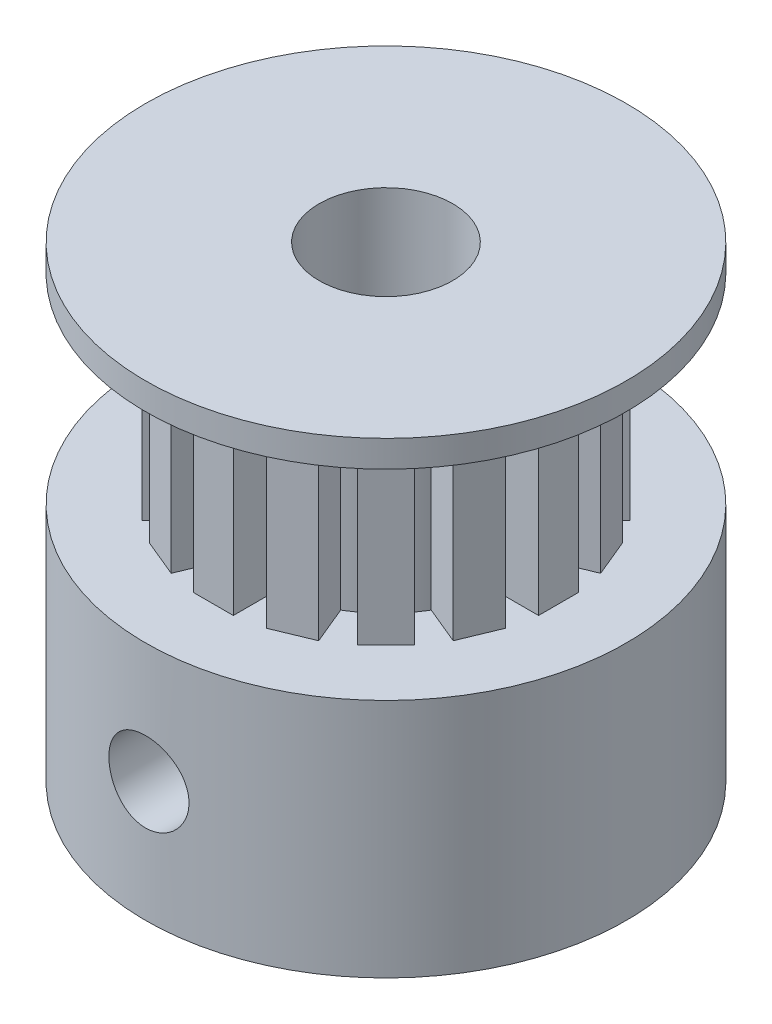
SolidWorks part; units mm, degrees
material "Liga 1060"
ref_plane "Plano frontal" through (0, 0, 0) normal (0, 0, 1) x (1, 0, 0)
ref_plane "Plano superior" through (0, 0, 0) normal (0, 1, 0) x (1, 0, 0)
ref_plane "Plano direito" through (0, 0, 0) normal (1, 0, 0) x (0, 0, -1)
sketch "Esboço1" plane through (0, 0, 0) normal (0, 0, 1) x (1, 0, 0)
  line L0 (0, 17.5) -> (0, 0)
  line L3 (-5, 0) -> (0, 0)
  line L7 (-9, 9) -> (-5, 9)
  line L8 (-9, 9) -> (-9, 8)
  line L11 (-9, 8) -> (-9, 0)
  line L12 (-9, 0) -> (-5, 0)
  line L14 (-5, 16.5) -> (-5, 9)
  line L19 (-9, 17.5) -> (0, 17.5)
  line L20 (-9, 17.5) -> (-9, 16.5)
  line L21 (-9, 16.5) -> (-5, 16.5)
  point P4 (0, 4)
  point P9 (0, 8.5)
  point P14 (0, 12.75)
  point P19 (0, 17)
  dimension "D1" = 1
  dimension "D2" = 5
  dimension "D4" = 9
  dimension "D5" = 7.5
revolve "Revolução1" add sketch "Esboço1" angle 360 about L0
sketch "Esboço2" plane through (0, 17.5, 0) normal (0, 1, 0) x (1, 0, 0)
  circle A0 centre (0, 0) radius 2.5
  dimension "D1" = 5
extrude "Corte-extrusão1" cut sketch "Esboço2" against normal blind 20
sketch "Esboço4" plane through (0, 17.5, 0) normal (0, 1, 0) x (1, 0, 0)
  line L0 (0.3446, 2.7919) -> (1.7305, 2.2178)
  line L1 (-0.75, 6.4653) -> (0.75, 6.4653)
  line L2 (-0.75, 6.4653) -> (-0.75, 2.7112)
  line L3 (-0.75, 2.7112) -> (0.75, 2.7112)
  line L4 (0.75, 6.4653) -> (0.75, 2.7112)
  line L5 (-0.75, 6.4653) -> (0.75, 2.7112) construction
  line L6 (-0.75, 2.7112) -> (0.75, 6.4653) construction
  line L7 (3.1671, 5.6861) -> (1.7305, 2.2178)
  line L8 (1.7812, 6.2601) -> (3.1671, 5.6861)
  line L9 (1.7812, 6.2601) -> (0.3446, 2.7919)
  line L10 (1.3868, 2.4475) -> (2.4475, 1.3868)
  line L11 (5.102, 4.0413) -> (2.4475, 1.3868)
  line L12 (4.0413, 5.102) -> (5.102, 4.0413)
  line L13 (4.0413, 5.102) -> (1.3868, 2.4475)
  line L14 (2.2178, 1.7305) -> (2.7919, 0.3446)
  line L15 (6.2601, 1.7812) -> (2.7919, 0.3446)
  line L16 (5.6861, 3.1671) -> (6.2601, 1.7812)
  line L17 (5.6861, 3.1671) -> (2.2178, 1.7305)
  line L18 (2.7112, 0.75) -> (2.7112, -0.75)
  line L19 (6.4653, -0.75) -> (2.7112, -0.75)
  line L20 (6.4653, 0.75) -> (6.4653, -0.75)
  line L21 (6.4653, 0.75) -> (2.7112, 0.75)
  line L22 (2.7919, -0.3446) -> (2.2178, -1.7305)
  line L23 (5.6861, -3.1671) -> (2.2178, -1.7305)
  line L24 (6.2601, -1.7812) -> (5.6861, -3.1671)
  line L25 (6.2601, -1.7812) -> (2.7919, -0.3446)
  line L26 (2.4475, -1.3868) -> (1.3868, -2.4475)
  line L27 (4.0413, -5.102) -> (1.3868, -2.4475)
  line L28 (5.102, -4.0413) -> (4.0413, -5.102)
  line L29 (5.102, -4.0413) -> (2.4475, -1.3868)
  line L30 (1.7305, -2.2178) -> (0.3446, -2.7919)
  line L31 (1.7812, -6.2601) -> (0.3446, -2.7919)
  line L32 (3.1671, -5.6861) -> (1.7812, -6.2601)
  line L33 (3.1671, -5.6861) -> (1.7305, -2.2178)
  line L34 (0.75, -2.7112) -> (-0.75, -2.7112)
  line L35 (-0.75, -6.4653) -> (-0.75, -2.7112)
  line L36 (0.75, -6.4653) -> (-0.75, -6.4653)
  line L37 (0.75, -6.4653) -> (0.75, -2.7112)
  line L38 (-0.3446, -2.7919) -> (-1.7305, -2.2178)
  line L39 (-3.1671, -5.6861) -> (-1.7305, -2.2178)
  line L40 (-1.7812, -6.2601) -> (-3.1671, -5.6861)
  line L41 (-1.7812, -6.2601) -> (-0.3446, -2.7919)
  line L42 (-1.3868, -2.4475) -> (-2.4475, -1.3868)
  line L43 (-5.102, -4.0413) -> (-2.4475, -1.3868)
  line L44 (-4.0413, -5.102) -> (-5.102, -4.0413)
  line L45 (-4.0413, -5.102) -> (-1.3868, -2.4475)
  line L46 (-2.2178, -1.7305) -> (-2.7919, -0.3446)
  line L47 (-6.2601, -1.7812) -> (-2.7919, -0.3446)
  line L48 (-5.6861, -3.1671) -> (-6.2601, -1.7812)
  line L49 (-5.6861, -3.1671) -> (-2.2178, -1.7305)
  line L50 (-2.7112, -0.75) -> (-2.7112, 0.75)
  line L51 (-6.4653, 0.75) -> (-2.7112, 0.75)
  line L52 (-6.4653, -0.75) -> (-6.4653, 0.75)
  line L53 (-6.4653, -0.75) -> (-2.7112, -0.75)
  line L54 (-2.7919, 0.3446) -> (-2.2178, 1.7305)
  line L55 (-5.6861, 3.1671) -> (-2.2178, 1.7305)
  line L56 (-6.2601, 1.7812) -> (-5.6861, 3.1671)
  line L57 (-6.2601, 1.7812) -> (-2.7919, 0.3446)
  line L58 (-2.4475, 1.3868) -> (-1.3868, 2.4475)
  line L59 (-4.0413, 5.102) -> (-1.3868, 2.4475)
  line L60 (-5.102, 4.0413) -> (-4.0413, 5.102)
  line L61 (-5.102, 4.0413) -> (-2.4475, 1.3868)
  line L62 (-1.7305, 2.2178) -> (-0.3446, 2.7919)
  line L63 (-1.7812, 6.2601) -> (-0.3446, 2.7919)
  line L64 (-3.1671, 5.6861) -> (-1.7812, 6.2601)
  line L65 (-3.1671, 5.6861) -> (-1.7305, 2.2178)
  point P4 (0, 4.5883)
  point P68 (0, 0)
  dimension "D1" = 1.5
  dimension "D2" = 16
extrude "Ressalto-extrusão1" add sketch "Esboço4" against normal blind 8.5 contours L13 L7 L8 L9 L4 L3 L0 L10 | L17 L11 L12 L13 L7 L0 L10 L14 | L21 L15 L16 L17 L11 L10 L14 L18 | L2 L63 L62 L3 L0 L9 L4 L1 | L64 L65 L59 L58 L62 L3 L2 L63 | L65 L59 L60 L61 L55 L54 L58 L62 | L61 L55 L56 L57 L51 L50 L54 L58 | L57 L51 L52 L53 L47 L46 L50 L54 | L53 L47 L48 L49 L43 L42 L46 L50 | L49 L43 L44 L45 L39 L38 L42 L46 | L45 L39 L40 L41 L35 L34 L38 L42 | L41 L35 L36 L37 L31 L30 L34 L38 | L37 L31 L32 L33 L27 L26 L30 L34 | L33 L27 L28 L29 L23 L22 L26 L30 | L29 L23 L24 L25 L19 L18 L22 L26 | L25 L19 L20 L21 L15 L14 L18 L22
sketch "Esboço5" plane through (0, 0, 0) normal (0, 0, 1) x (1, 0, 0)
  circle A0 centre (0, 4.5) radius 1.5
  dimension "D2" = 3
  dimension "D1" = 4.5
extrude "Corte-extrusão2" cut sketch "Esboço5" against normal blind 10 and the other way blind 10
